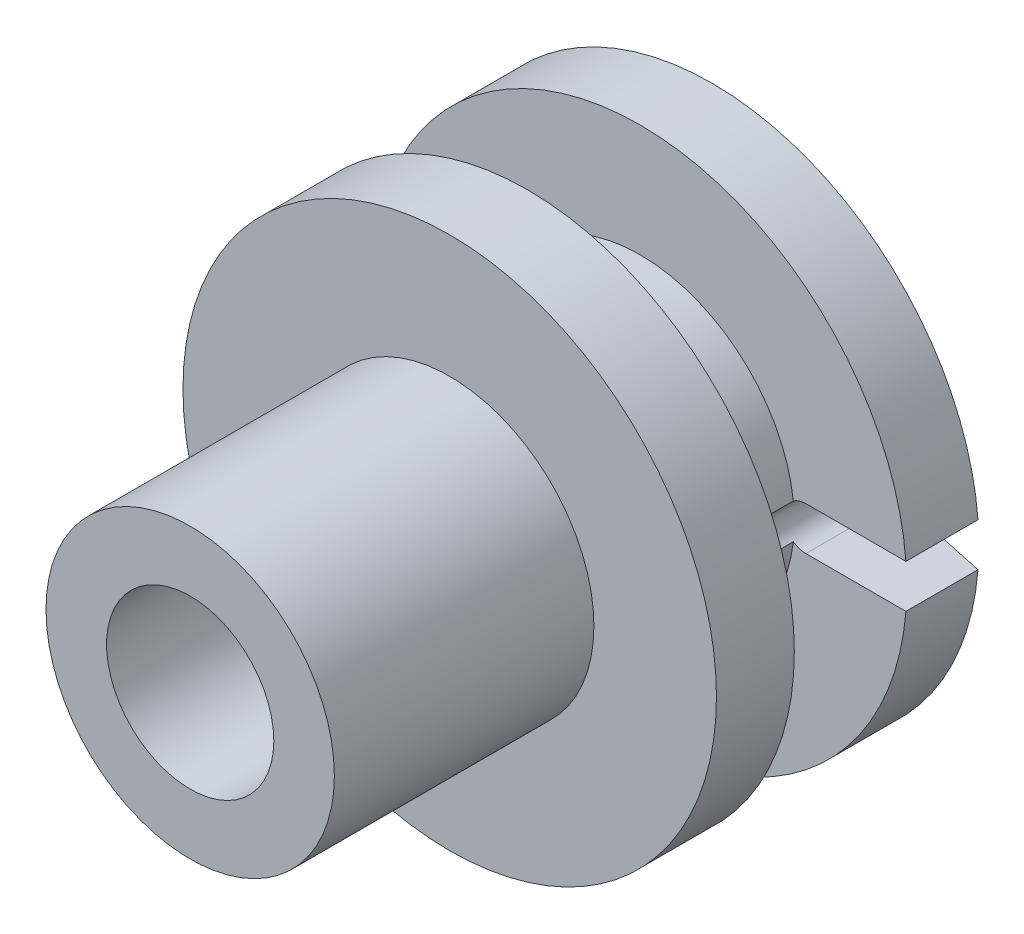
SolidWorks part; units mm, degrees
ref_plane "Front Plane" through (0, 0, 0) normal (0, 0, 1) x (1, 0, 0)
ref_plane "Top Plane" through (0, 0, 0) normal (0, 1, 0) x (1, 0, 0)
ref_plane "Right Plane" through (0, 0, 0) normal (1, 0, 0) x (0, 0, -1)
sketch "Sketch1" plane through (0, 0, 0) normal (0, 0, 1) x (1, 0, 0)
  circle A0 centre (0, 0) radius 9.25
  dimension "D1" = 18.5
extrude "Boss-Extrude1" add sketch "Sketch1" along normal blind 2.5
sketch "Sketch2" plane through (0, 0, 2.5) normal (0, 0, 1) x (1, 0, 0)
  circle A0 centre (0, 0) radius 5.35
  circle A1 centre (0, 0) radius 9.25 construction
  dimension "D1" = 3.9
extrude "Boss-Extrude2" add sketch "Sketch2" along normal blind 3.9
sketch "Sketch3" plane through (0, 0, 6.4) normal (0, 0, 1) x (1, 0, 0)
  circle A0 centre (0, 0) radius 9.25
  dimension "D1" = 18.5
extrude "Boss-Extrude3" add sketch "Sketch3" along normal blind 2.7
sketch "Sketch4" plane through (0, 0, 9.1) normal (0, 0, 1) x (1, 0, 0)
  circle A0 centre (0, 0) radius 5
  dimension "D1" = 10
extrude "Boss-Extrude4" add sketch "Sketch4" along normal blind 9
sketch "Sketch6" plane through (0, 0, 0) normal (0, 1, 0) x (1, 0, 0)
  line L0 (0, 0) -> (0, 2)
  line L1 (0, 2) -> (9.25, 0)
  line L2 (9.25, 0) -> (0, 0)
  dimension "D1" = 2
revolve "Revolve1" add sketch "Sketch6" angle 360 about L0
sketch "Sketch7" plane through (0, 0, 0) normal (0, 0, 1) x (1, 0, 0)
  line L0 (-5.75, 0.75) -> (-9.2195, 0.75)
  line L1 (-5.75, -0.75) -> (-9.2195, -0.75)
  line L2 (0, 9.25) -> (0, -9.25) construction
  line L3 (5.75, -0.75) -> (9.2195, -0.75)
  line L4 (5.75, 0.75) -> (9.2195, 0.75)
  arc A0 (-5.75, -0.75) -> (-5.75, 0.75) centre (-5.75, 0) ccw
  circle A1 centre (0, 0) radius 5 construction
  circle A2 centre (0, 0) radius 9.25 construction
  arc A3 (-9.2195, 0.75) -> (-9.2195, -0.75) centre (0, 0) ccw
  arc A4 (9.2195, 0.75) -> (9.2195, -0.75) centre (0, 0) cw
  arc A5 (5.75, -0.75) -> (5.75, 0.75) centre (5.75, 0) cw
  dimension "D1" = 1.5
extrude "Cut-Extrude1" cut sketch "Sketch7" against normal mid plane 9
sketch "Sketch8" plane through (0, 0, 18.1) normal (0, 0, 1) x (1, 0, 0)
  circle A0 centre (0, 0) radius 2.9
  dimension "D1" = 5.8
extrude "Cut-Extrude2" cut sketch "Sketch8" against normal blind 12
